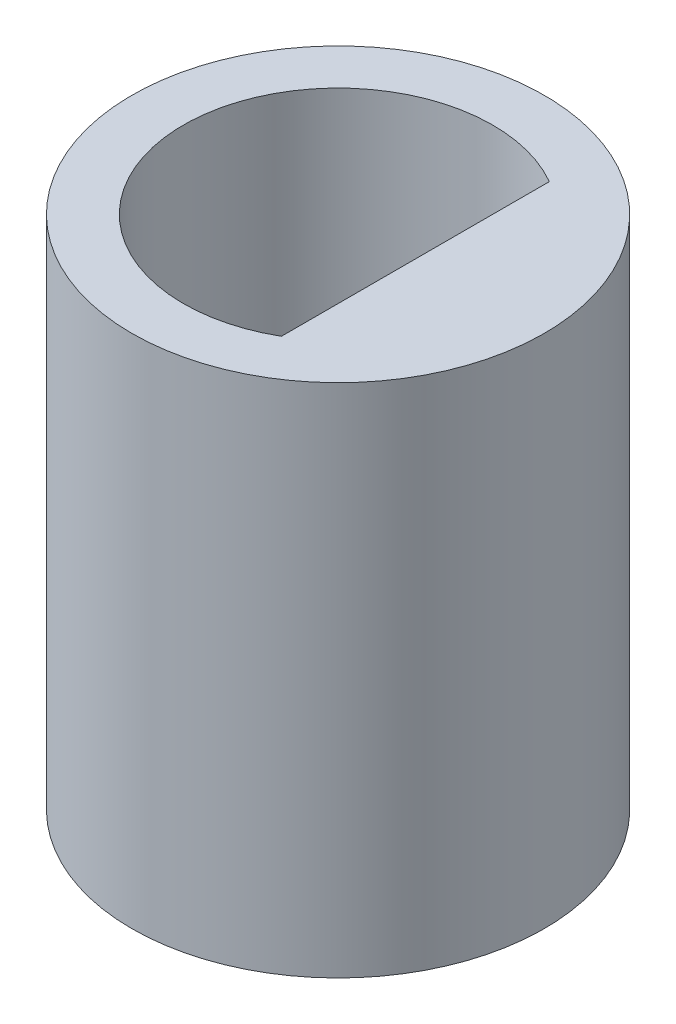
SolidWorks part; units mm, degrees
ref_plane "Front Plane" through (0, 0, 0) normal (0, 0, 1) x (1, 0, 0)
ref_plane "Top Plane" through (0, 0, 0) normal (0, 1, 0) x (1, 0, 0)
ref_plane "Right Plane" through (0, 0, 0) normal (1, 0, 0) x (0, 0, -1)
sketch "Sketch1" plane through (0, 0, 0) normal (0, 1, 0) x (1, 0, 0)
  line L0 (1.5, 2.5981) -> (1.5, -2.5981)
  circle A0 centre (0, 0) radius 4
  arc A1 (1.5, 2.5981) -> (1.5, -2.5981) centre (0, 0) ccw
  dimension "D1" = 8
  dimension "D2" = 3
  dimension "D3" = 1.5
extrude "Boss-Extrude1" add sketch "Sketch1" along normal blind 10
